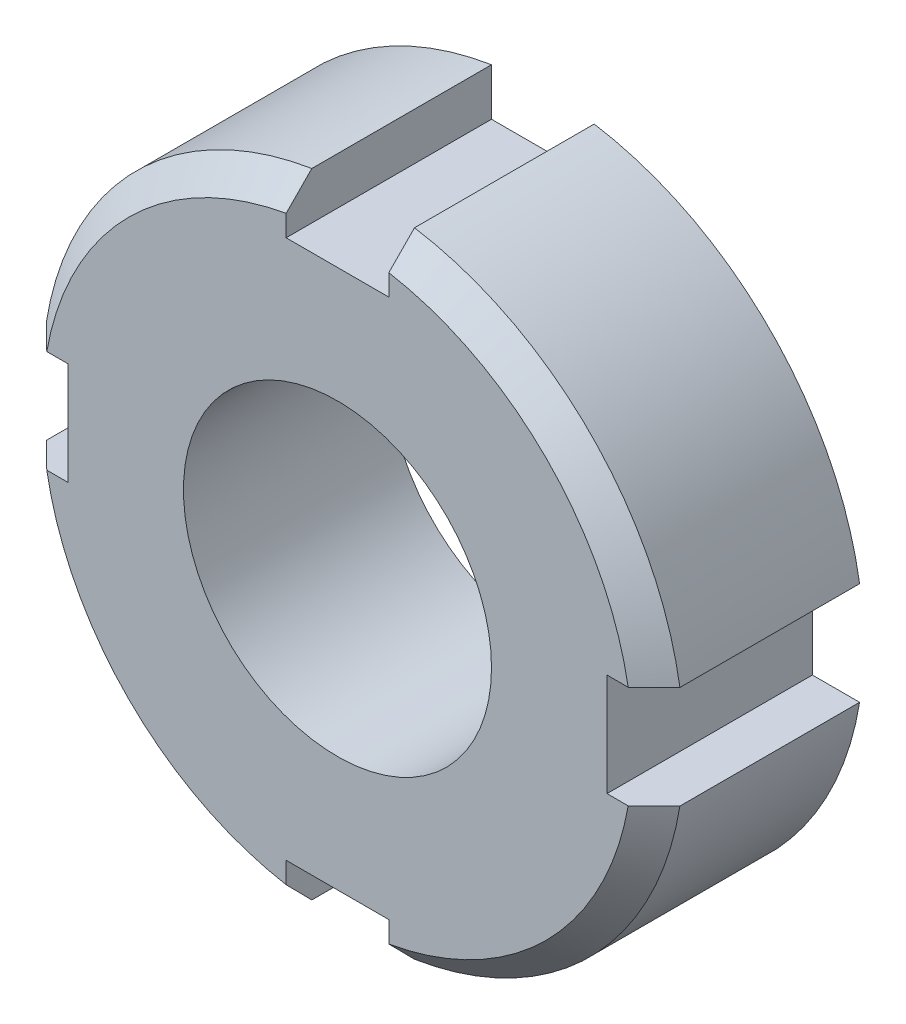
SolidWorks part; units mm, degrees
ref_plane "Front Plane" through (0, 0, 0) normal (0, 0, 1) x (1, 0, 0)
ref_plane "Top Plane" through (0, 0, 0) normal (0, 1, 0) x (1, 0, 0)
ref_plane "Right Plane" through (0, 0, 0) normal (1, 0, 0) x (0, 0, -1)
sketch "Sketch1" plane through (0, 0, 0) normal (0, 0, 1) x (1, 0, 0)
  circle A0 centre (0, 0) radius 12.5
  dimension "D1" = 25
extrude "Boss-Extrude1" add sketch "Sketch1" along normal blind 8
sketch "Sketch2" plane through (0, 0, 8) normal (0, 0, 1) x (1, 0, 0)
  circle A0 centre (0, 0) radius 6
  dimension "D1" = 12
extrude "Cut-Extrude1" cut sketch "Sketch2" against normal through all
sketch "Sketch3" plane through (0, 0, 8) normal (0, 0, 1) x (1, 0, 0)
  line L0 (0, 15.1862) -> (0, 0) construction
  line L1 (14.5, 2) -> (10.5, 2)
  line L2 (-2, 14.5) -> (2, 14.5)
  line L3 (-2, 14.5) -> (-2, 10.5)
  line L4 (-2, 10.5) -> (2, 10.5)
  line L5 (2, 14.5) -> (2, 10.5)
  line L6 (-2, 14.5) -> (2, 10.5) construction
  line L7 (-2, 10.5) -> (2, 14.5) construction
  line L8 (14.5, 2) -> (14.5, -2)
  line L9 (10.5, 2) -> (10.5, -2)
  line L10 (14.5, -2) -> (10.5, -2)
  line L11 (2, -14.5) -> (2, -10.5)
  line L12 (2, -14.5) -> (-2, -14.5)
  line L13 (2, -10.5) -> (-2, -10.5)
  line L14 (-2, -14.5) -> (-2, -10.5)
  line L15 (-14.5, -2) -> (-10.5, -2)
  line L16 (-14.5, -2) -> (-14.5, 2)
  line L17 (-10.5, -2) -> (-10.5, 2)
  line L18 (-14.5, 2) -> (-10.5, 2)
  circle A0 centre (0, 0) radius 12.5 construction
  point P3 (0, 12.5)
  point P25 (0, 0)
  dimension "D1" = 4
  dimension "D2" = 2
  dimension "D3" = 4
extrude "Cut-Extrude2" cut sketch "Sketch3" against normal through all
chamfer "Chamfer1" distance 1 angle 45 4 edges at (8.8388, 8.8388, 8) (8.8388, -8.8388, 8) (-8.8388, -8.8388, 8) (-8.8388, 8.8388, 8)
